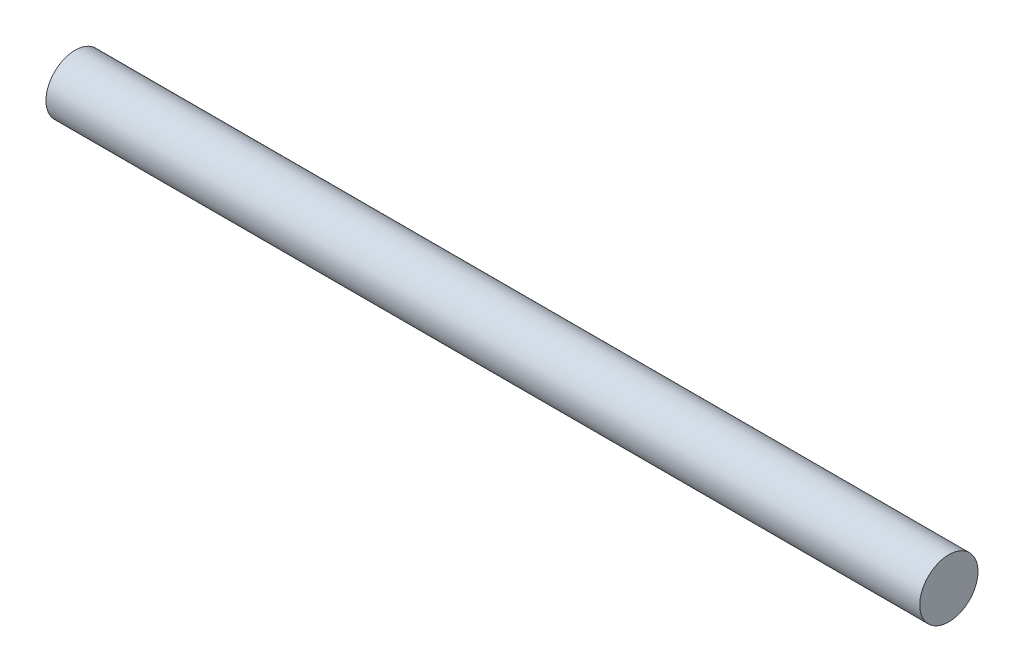
SolidWorks part; units mm, degrees
ref_plane "Front Plane" through (0, 0, 0) normal (0, 0, 1) x (1, 0, 0)
ref_plane "Top Plane" through (0, 0, 0) normal (0, 1, 0) x (1, 0, 0)
ref_plane "Right Plane" through (0, 0, 0) normal (1, 0, 0) x (0, 0, -1)
sketch "Sketch1" plane through (0, 0, 0) normal (1, 0, 0) x (0, 0, -1)
  circle A0 centre (0, 0) radius 5
extrude "Boss-Extrude1" add sketch "Sketch1" along normal blind 150
cosmetic thread "Cosmetic Thread1" parameters "D1"=10, "D2"=8.344
cosmetic thread "Cosmetic Thread2" parameters "D1"=10, "D2"=8.344
sketch "Sketch2" plane through (0, 0, 0) normal (0, 1, 0) x (1, 0, 0)
  line L0 (150, -5) -> (150, 5) construction
  circle A0 centre (65, 0) radius 1.65
  dimension "D1" = 3.3
  dimension "D2" = 85
